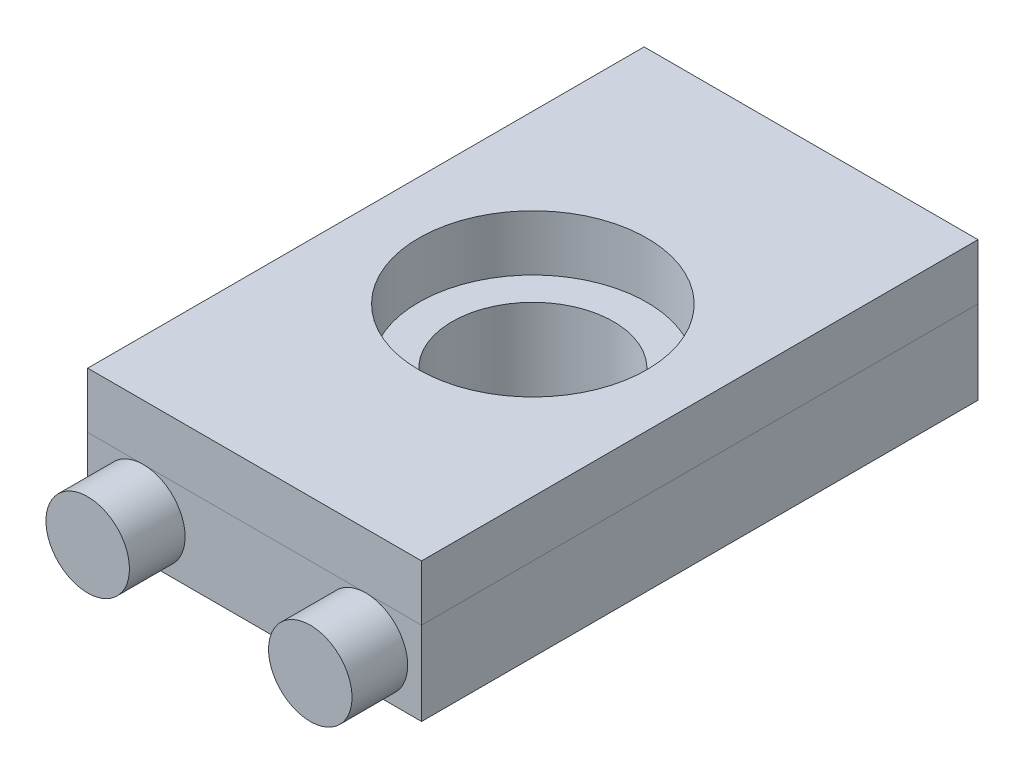
SolidWorks part; units mm, degrees
ref_plane "前视基准面" through (0, 0, 0) normal (0, 0, 1) x (1, 0, 0)
ref_plane "上视基准面" through (0, 0, 0) normal (0, 1, 0) x (1, 0, 0)
ref_plane "右视基准面" through (0, 0, 0) normal (1, 0, 0) x (0, 0, -1)
other "Configuration Table"
sketch "草图1" plane through (0, 0, 0) normal (0, 1, 0) x (1, 0, 0)
  line L0 (6, 20) -> (6, 0) construction
  line L1 (0, 0) -> (12, 0)
  line L2 (0, 0) -> (0, 20)
  line L3 (0, 20) -> (12, 20)
  line L4 (12, 0) -> (12, 20)
  circle A0 centre (6, 10) radius 2.9
  circle A1 centre (6, 10) radius 4.1
  dimension "D3" = 5.8
  dimension "D4" = 8.2
  dimension "D1" = 12
  dimension "D2" = 20
  dimension "D5" = 10
extrude "凸台-拉伸1" add sketch "草图1" along normal blind 3 contours L2 L1 L4 L3 | A0
sketch "草图3" plane through (0, 3, 0) normal (0, 1, 0) x (1, 0, 0)
  line L1 (0, 20) -> (12, 20)
  line L2 (0, 20) -> (0, 0)
  line L3 (0, 0) -> (12, 0)
  line L4 (12, 20) -> (12, 0)
  circle A0 centre (6, 10) radius 4.1
  circle A1 centre (6, 10) radius 2.9 construction
  circle A2 centre (6, 10) radius 2.9
  line M6 (12, 20) -> (0, 20)
  line M7 (0, 20) -> (0, 0)
  line M8 (0, 0) -> (12, 0)
  line M9 (12, 0) -> (12, 20)
  dimension "D1" = 8.2
extrude "凸台-拉伸2" add sketch "草图3" along normal blind 2 contours A0 M9 M6 M7 M8
sketch "草图7" plane through (0, 0, 0) normal (0, 0, 1) x (1, 0, 0)
  line L0 (12, 1.5) -> (0, 1.5) construction
  line L1 (12, 3) -> (12, 0) construction
  line L2 (0, 3) -> (0, 0) construction
  line L3 (6, 5) -> (6, 0) construction
  line L4 (0, 5) -> (12, 5) construction
  line L5 (0, 0) -> (12, 0) construction
  circle A0 centre (2, 1.5) radius 1.5
  circle A2 centre (10, 1.5) radius 1.5
  dimension "D1" = 3
  dimension "D2" = 4
extrude "凸台-拉伸3" add sketch "草图7" along normal blind 2
